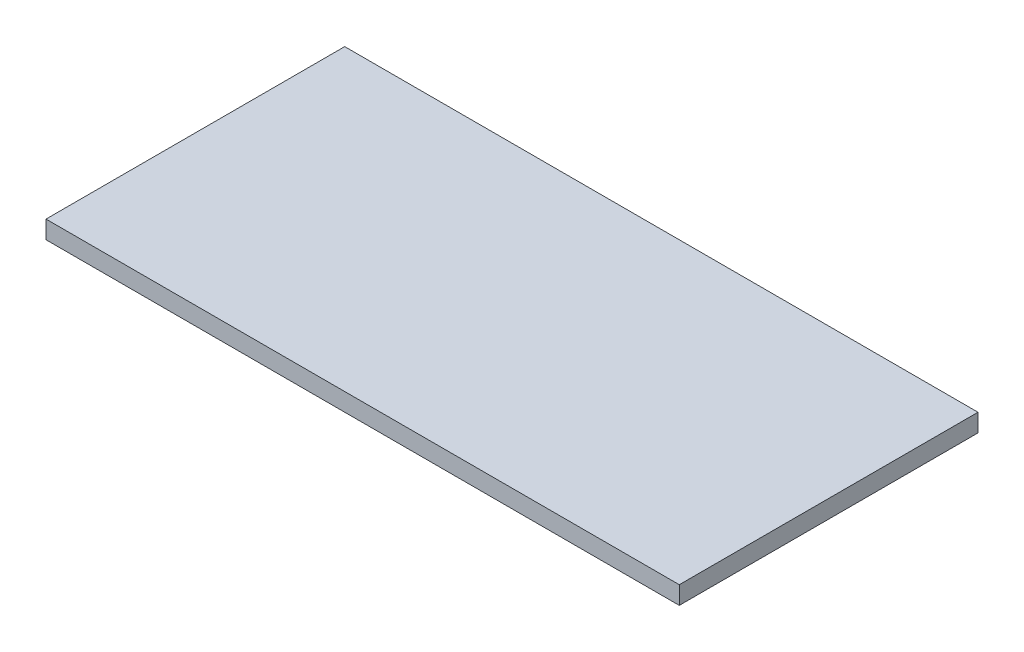
SolidWorks part; units mm, degrees
ref_plane "Front Plane" through (0, 0, 0) normal (0, 0, 1) x (1, 0, 0)
ref_plane "Top Plane" through (0, 0, 0) normal (0, 1, 0) x (1, 0, 0)
ref_plane "Right Plane" through (0, 0, 0) normal (1, 0, 0) x (0, 0, -1)
sketch "Sketch1" plane through (0, 0, 0) normal (0, 1, 0) x (1, 0, 0)
  line L1 (0, 0) -> (212, 0)
  line L2 (0, 0) -> (0, 100)
  line L3 (0, 100) -> (212, 100)
  line L4 (212, 0) -> (212, 100)
  dimension "D1" = 212
  dimension "D2" = 100
extrude "Boss-Extrude1" add sketch "Sketch1" along normal blind 6
equation "\"BoardThickness\" = 6"
equation "\"D1@Boss-Extrude1\"=\"BoardThickness\""
equation "\"D1@Sketch1\"=200+\"BoardThickness\"*2"
